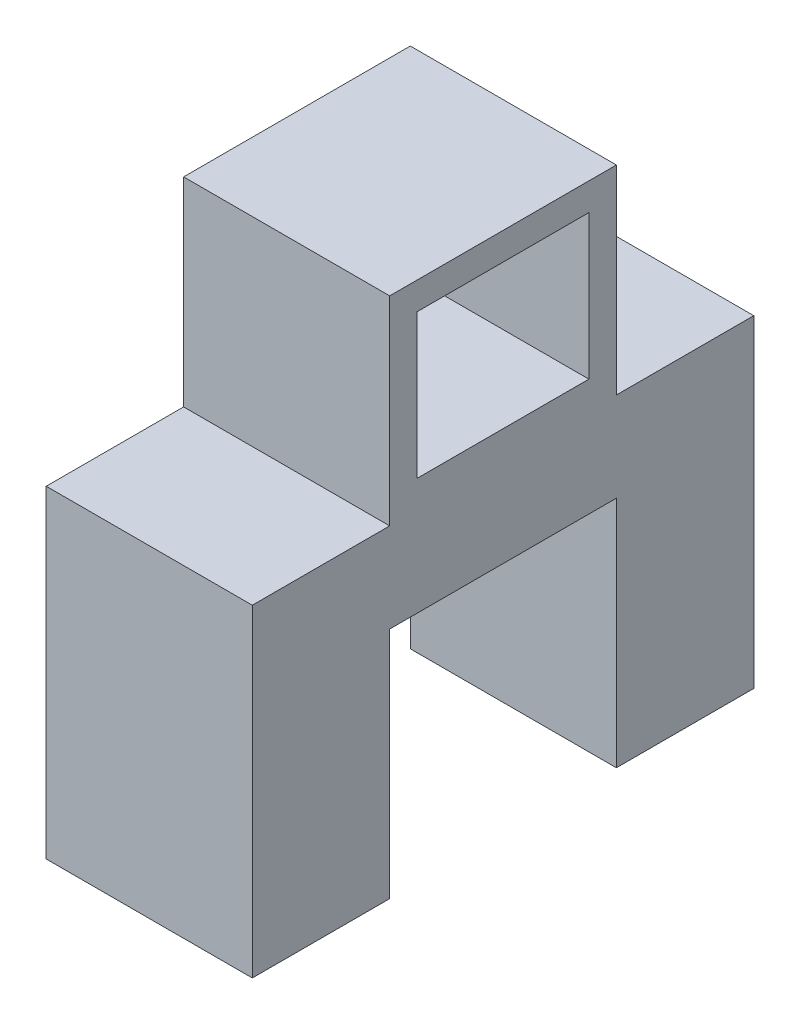
SolidWorks part; units mm, degrees
ref_plane "Front Plane" through (0, 0, 0) normal (0, 0, 1) x (1, 0, 0)
ref_plane "Top Plane" through (0, 0, 0) normal (0, 1, 0) x (1, 0, 0)
ref_plane "Right Plane" through (0, 0, 0) normal (1, 0, 0) x (0, 0, -1)
sketch "Sketch1" plane through (0, 0, 0) normal (1, 0, 0) x (0, 0, -1)
  line L0 (-2, 2) -> (-2, -12.5)
  line L1 (0, 0) -> (12.5, 0)
  line L2 (0, 0) -> (0, -10.5)
  line L3 (0, -10.5) -> (12.5, -10.5)
  line L4 (12.5, 0) -> (12.5, -10.5)
  line L6 (14.5, 2) -> (14.5, -12.5)
  line L7 (-2, 2) -> (14.5, 2)
  line L8 (-2, -12.5) -> (-12, -12.5)
  line L9 (-12, -12.5) -> (-12, -36)
  line L10 (14.5, -12.5) -> (24.5, -12.5)
  line L11 (24.5, -12.5) -> (24.5, -36)
  line L12 (-12, -36) -> (-2, -36)
  line L13 (-2, -36) -> (-2, -19.0034)
  line L14 (-2, -12.5) -> (14.5, -12.5) construction
  line L15 (-2, -19.0034) -> (14.5, -19.0034)
  line L16 (14.5, -19.0034) -> (14.5, -36)
  line L17 (14.5, -36) -> (24.5, -36)
  dimension "D1" = 12.5
  dimension "D2" = 10.5
  dimension "D4" = 23.5
  dimension "D5" = 23.5
  dimension "D6" = 10
  dimension "D7" = 10
  dimension "D8" = 10
  dimension "D3" = 2
extrude "Boss-Extrude1" add sketch "Sketch1" along normal blind 15
